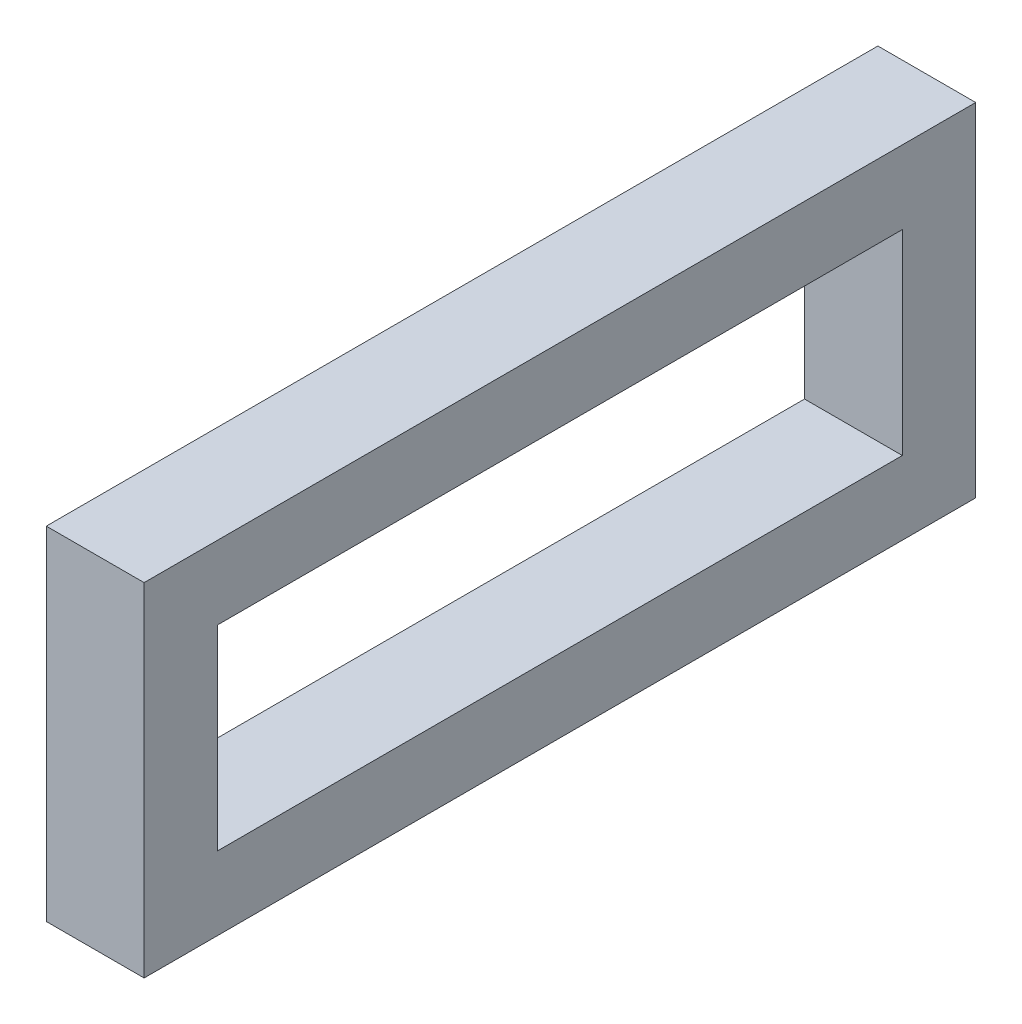
SolidWorks part; units mm, degrees
ref_plane "Front Plane" through (0, 0, 0) normal (0, 0, 1) x (1, 0, 0)
ref_plane "Top Plane" through (0, 0, 0) normal (0, 1, 0) x (1, 0, 0)
ref_plane "Right Plane" through (0, 0, 0) normal (1, 0, 0) x (0, 0, -1)
sketch "Sketch2" plane through (0, 0, 0) normal (1, 0, 0) x (0, 0, -1)
  line L1 (-85, 35) -> (85, 35)
  line L2 (-85, 35) -> (-85, -35)
  line L3 (-85, -35) -> (85, -35)
  line L4 (85, 35) -> (85, -35)
  line L5 (-85, 35) -> (85, -35) construction
  line L6 (-85, -35) -> (85, 35) construction
  line L7 (-70, 20) -> (70, 20)
  line L8 (-70, 20) -> (-70, -20)
  line L9 (-70, -20) -> (70, -20)
  line L10 (70, 20) -> (70, -20)
  line L11 (-70, 20) -> (70, -20) construction
  line L12 (-70, -20) -> (70, 20) construction
  point P0 (0, 0)
  point P6 (0, 0)
  dimension "D1" = 170
  dimension "D2" = 70
  dimension "D3" = 140
  dimension "D4" = 40
extrude "Boss-Extrude1" add sketch "Sketch2" along normal blind 20
